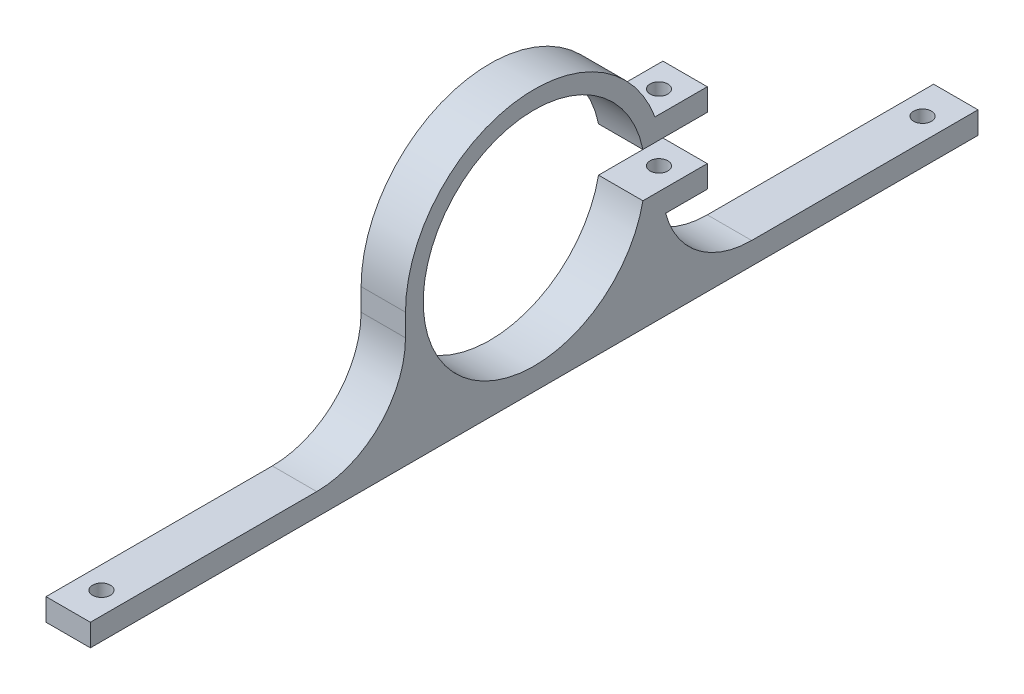
SolidWorks part; units mm, degrees
ref_plane "Alzado" through (0, 0, 0) normal (0, 0, 1) x (1, 0, 0)
ref_plane "Planta" through (0, 0, 0) normal (0, 1, 0) x (1, 0, 0)
ref_plane "Vista lateral" through (0, 0, 0) normal (1, 0, 0) x (0, 0, -1)
sketch "Croquis2" plane through (0, 0, 0) normal (1, 0, 0) x (0, 0, -1)
  line L0 (-100, 0) -> (100, 0)
  line L1 (-100, 0) -> (-100, 5)
  line L2 (100, 0) -> (100, 5)
  line L3 (0, 0) -> (0, 30) construction
  line L4 (-29, 30) -> (-29, 25)
  line L5 (-49, 5) -> (-100, 5)
  line L6 (29, 30) -> (29, 25) construction
  line L7 (49, 5) -> (100, 5)
  line L8 (29, 30) -> (39, 30) construction
  line L9 (39, 35) -> (39, 25) construction
  line L10 (39, 35) -> (24.4949, 35)
  line L11 (39, 25) -> (24.4949, 25)
  line L12 (39, 25) -> (39, 20) construction
  line L13 (39, 25) -> (39, 20)
  line L14 (39, 20) -> (29.6351, 20)
  line L15 (39, 35) -> (39, 40) construction
  line L16 (39, 35) -> (39, 40)
  line L17 (39, 40) -> (27.2213, 40)
  circle A2 centre (0, 30) radius 25
  circle A3 centre (0, 30) radius 29
  arc A4 (49, 5) -> (29, 25) centre (49, 25) cw
  arc A5 (-49, 5) -> (-29, 25) centre (-49, 25) ccw
  point P4 (0, 0)
  point P22 (39, 30)
  dimension "D1" = 20
extrude "Saliente-Extruir1" add sketch "Croquis2" along normal blind 10 contours A5 L5 L1 L0 L2 L7 A4 L11 A3 L4 | A3 L10 L16 L17 | A4 L14 L13 L11 | L10 A3 L11 A2
sketch "Croquis4" plane through (0, 40, 0) normal (0, 1, 0) x (1, 0, 0)
  line L0 (0, 27.2213) -> (10, 39) construction
  circle A0 centre (5, 33.1107) radius 2
extrude "Cortar-Extruir1" cut sketch "Croquis4" against normal blind 23
sketch "Croquis5" plane through (0, 5, 0) normal (0, 1, 0) x (1, 0, 0)
  line L0 (0, 0) -> (0, -92.5) construction
  line L1 (0, -49) -> (0, -100) construction
  line L2 (0, 0) -> (0, 92.5) construction
  line L3 (0, 49) -> (0, 100) construction
  line L4 (0, -92.5) -> (10, -92.5) construction
  line L5 (10, -49) -> (10, -100) construction
  line L6 (0, 92.5) -> (10, 92.5) construction
  line L7 (10, 49) -> (10, 100) construction
  circle A0 centre (5, -92.5) radius 2
  circle A1 centre (5, 92.5) radius 2
extrude "Cortar-Extruir2" cut sketch "Croquis5" against normal blind 23
